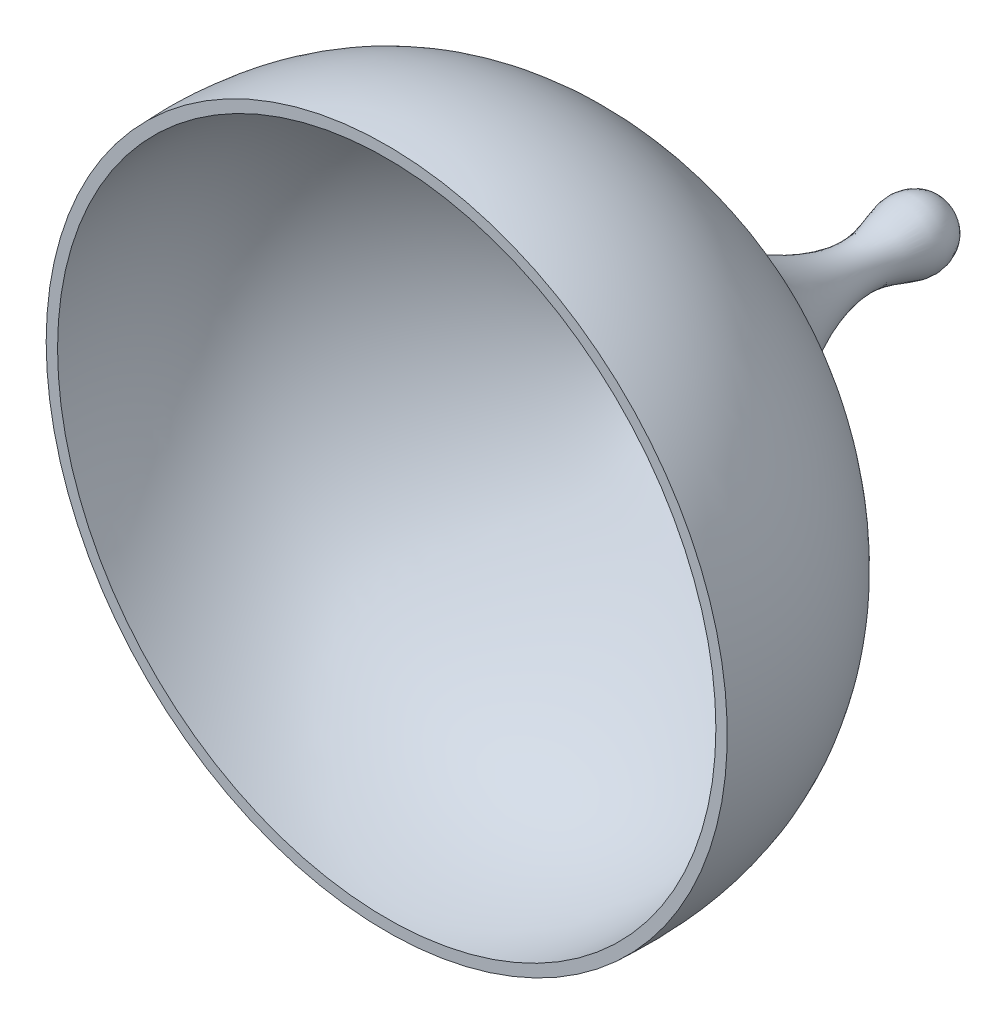
SolidWorks part; units mm, degrees
ref_plane "Plano frontal" through (0, 0, 0) normal (0, 0, 1) x (1, 0, 0)
ref_plane "Plano superior" through (0, 0, 0) normal (0, 1, 0) x (1, 0, 0)
ref_plane "Plano direito" through (0, 0, 0) normal (1, 0, 0) x (0, 0, -1)
sketch "Esboço1" plane through (0, 0, 0) normal (0, 1, 0) x (1, 0, 0)
  line L0 (0, -17.5) -> (-10.765, -17.5)
  line L1 (0, 0) -> (0, -17.5) construction
  line L2 (0, 0) -> (0, -17.5)
  line L3 (-10.765, -17.5) -> (-10.405, -17.5)
  spline S0 degree 3 poles (-10.765, -17.5) (-10.9123, -14.5978) (-9.4295, -10.1485) (-3.0883, -7.3315) (-1.7573, -5.8238) (-0.8875, -4.0549) (-0.3683, -2.3946) (-1.3367, -0.7718) (-0.555, 0.2937) (0, 0) knots 0 0 0 0 0.375613 0.73604 0.831842 0.850123 0.91885 0.959344 1 1 1 1
  spline S1 degree 3 poles (-10.405, -17.5) (-10.4919, -15.9729) (-10.2899, -13.1938) (-7.8316, -10.5169) (-5.3988, -8.7867) (-3.0791, -7.5573) (-1.1327, -5.7863) (-0.1233, -3.4623) (-0.4978, -1.6963) (-0.6386, -0.7152) (-0.3863, -0.4383) (-0.133, -0.4471) (0, -0.4552) knots 0 0 0 0 0.216943 0.356231 0.487331 0.631027 0.717014 0.849542 0.954579 0.967567 0.980973 1 1 1 1
  dimension "D1" = 10.765
  dimension "D2" = 17.5
  dimension "D3" = 0.36
revolve "Revolução7" add sketch "Esboço1" angle 360 about L1
